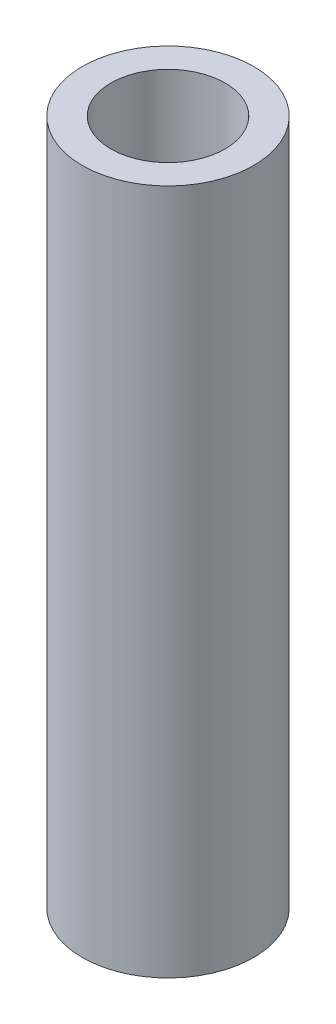
SolidWorks part; units mm, degrees
ref_plane "Front Plane" through (0, 0, 0) normal (0, 0, 1) x (1, 0, 0)
ref_plane "Top Plane" through (0, 0, 0) normal (0, 1, 0) x (1, 0, 0)
ref_plane "Right Plane" through (0, 0, 0) normal (1, 0, 0) x (0, 0, -1)
sketch "Sketch2" plane through (0, 0, 0) normal (0, 1, 0) x (1, 0, 0)
  circle A0 centre (0, 0) radius 5.715
  circle A1 centre (0, 0) radius 3.81
  dimension "D1" = 11.43
  dimension "D2" = 7.62
extrude "Boss-Extrude1" add sketch "Sketch2" along normal blind 45.72
